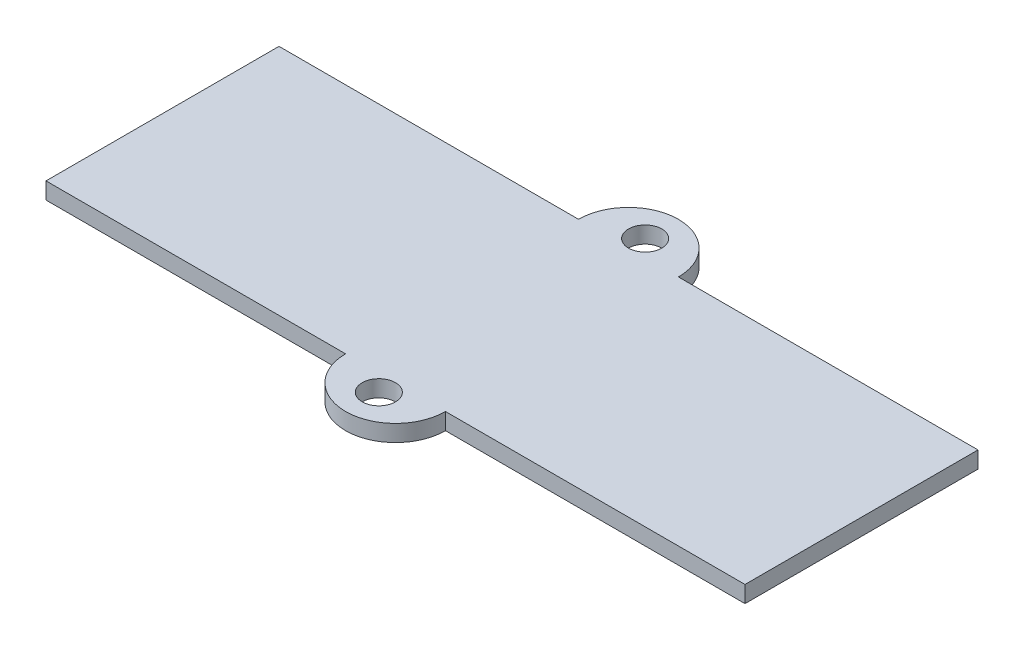
SolidWorks part; units mm, degrees
ref_plane "Front Plane" through (0, 0, 0) normal (0, 0, 1) x (1, 0, 0)
ref_plane "Top Plane" through (0, 0, 0) normal (0, 1, 0) x (1, 0, 0)
ref_plane "Right Plane" through (0, 0, 0) normal (1, 0, 0) x (0, 0, -1)
sketch "Sketch1" plane through (0, 0, 0) normal (0, 1, 0) x (1, 0, 0)
  line L0 (165.0828, -24.9903) -> (165.0828, 3.0097) construction
  line L1 (129.0828, -24.9903) -> (165.0828, -24.9903) construction
  line L2 (165.0828, 3.0097) -> (129.0828, 3.0097) construction
  line L3 (117.0828, 3.0097) -> (81.0828, 3.0097) construction
  line L4 (81.0828, 3.0097) -> (81.0828, -24.9903) construction
  line L5 (81.0828, -24.9903) -> (117.0828, -24.9903) construction
  line L6 (165.0828, -24.9903) -> (165.0828, 3.0097)
  line L7 (129.0828, -24.9903) -> (165.0828, -24.9903)
  line L8 (165.0828, 3.0097) -> (129.0828, 3.0097)
  line L9 (117.0828, 3.0097) -> (81.0828, 3.0097)
  line L10 (81.0828, 3.0097) -> (81.0828, -24.9903)
  line L11 (81.0828, -24.9903) -> (117.0828, -24.9903)
  arc A0 (129.0828, 3.0097) -> (117.0828, 3.0097) centre (123.0828, 3.0097) ccw construction
  arc A1 (117.0828, -24.9903) -> (129.0828, -24.9903) centre (123.0828, -24.9903) ccw construction
  arc A2 (129.0828, 3.0097) -> (117.0828, 3.0097) centre (123.0828, 3.0097) ccw
  arc A3 (117.0828, -24.9903) -> (129.0828, -24.9903) centre (123.0828, -24.9903) ccw
  circle A4 centre (123.0828, 5.0097) radius 2 construction
  circle A5 centre (123.0828, -26.9903) radius 2 construction
  circle A6 centre (123.0828, 5.0097) radius 2
  circle A7 centre (123.0828, -26.9903) radius 2
extrude "Boss-Extrude1" add sketch "Sketch1" along normal blind 2
